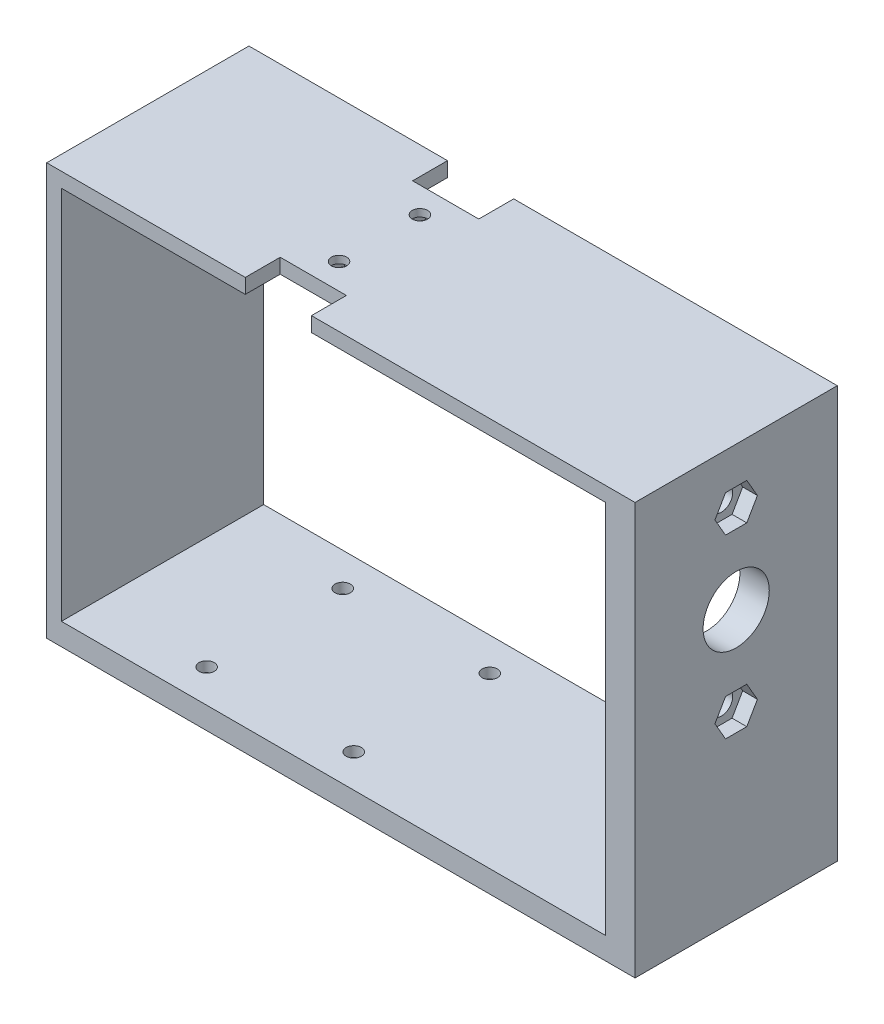
SolidWorks part; units mm, degrees
ref_plane "Front Plane" through (0, 0, 0) normal (0, 0, 1) x (1, 0, 0)
ref_plane "Top Plane" through (0, 0, 0) normal (0, 1, 0) x (1, 0, 0)
ref_plane "Right Plane" through (0, 0, 0) normal (1, 0, 0) x (0, 0, -1)
sketch "Sketch1" plane through (0, 0, 0) normal (1, 0, 0) x (0, 0, -1)
  line L1 (0, 0) -> (55, 0)
  line L2 (0, 0) -> (0, -112)
  line L3 (0, -112) -> (55, -112)
  line L4 (55, 0) -> (55, -112)
  dimension "D1" = 112
  dimension "D2" = 55
extrude "Boss-Extrude1" add sketch "Sketch1" along normal blind 160
sketch "Sketch2" plane through (0, 0, 0) normal (0, 0, 1) x (1, 0, 0)
  line L0 (160, 0) -> (0, 0) construction
  line L1 (4, -4) -> (152, -4)
  line L2 (4, -4) -> (4, -106)
  line L3 (4, -106) -> (152, -106)
  line L4 (152, -4) -> (152, -106)
  line L5 (160, 0) -> (160, -112) construction
  line L6 (160, -112) -> (0, -112) construction
  line L7 (0, 0) -> (0, -112) construction
  dimension "D1" = 4
  dimension "D2" = 8
  dimension "D3" = 6
  dimension "D4" = 4
extrude "Cut-Extrude1" cut sketch "Sketch2" against normal up to next
sketch "Sketch3" plane through (152, 0, 0) normal (-1, 0, 0) x (0, 0, 1)
  line L0 (-27.5, -106) -> (-27.5, -39) construction
  line L1 (-55, -106) -> (0, -106) construction
  line L2 (-27.5, -39) -> (-27.5, -15) construction
  line L3 (-27.5, -39) -> (0, -39) construction
  circle A0 centre (-27.5, -39) radius 9
  circle A1 centre (-27.5, -15) radius 3.05
  circle A2 centre (-27.5, -63) radius 3.05
  dimension "D3" = 6.1
  dimension "D4" = 18
  dimension "D1" = 67
  dimension "D2" = 24
extrude "Cut-Extrude2" cut sketch "Sketch3" against normal up to next
sketch "Sketch6" plane through (160, 0, 0) normal (1, 0, 0) x (0, 0, -1)
  line L0 (55, 0) -> (0, 0) construction
  line L1 (30.3868, -20) -> (33.2735, -15)
  line L2 (33.2735, -15) -> (30.3868, -10)
  line L3 (30.3868, -10) -> (24.6132, -10)
  line L4 (24.6132, -10) -> (21.7265, -15)
  line L5 (21.7265, -15) -> (24.6132, -20)
  line L6 (24.6132, -20) -> (30.3868, -20)
  line L8 (30.3868, -68) -> (33.2735, -63)
  line L9 (33.2735, -63) -> (30.3868, -58)
  line L10 (30.3868, -58) -> (24.6132, -58)
  line L11 (24.6132, -58) -> (21.7265, -63)
  line L12 (21.7265, -63) -> (24.6132, -68)
  line L13 (24.6132, -68) -> (30.3868, -68)
  circle A0 centre (27.5, -15) radius 5 construction
  circle A1 centre (27.5, -63) radius 5 construction
  dimension "D1" = 10
  dimension "D2" = 10
extrude "Cut-Extrude4" cut sketch "Sketch6" against normal blind 4
sketch "Sketch15" plane through (0, -112, 0) normal (0, -1, 0) x (-1, 0, 0)
  line L0 (0, 0) -> (0, 9) construction
  line L1 (0, 0) -> (0, 55) construction
  line L2 (0, 9) -> (-34.5, 9) construction
  line L3 (-34.5, 9) -> (-74.5, 9) construction
  line L4 (-4, 27.5) -> (-87.1996, 27.5) construction
  line L5 (-4, 55) -> (-4, 0) construction
  circle A0 centre (-34.5, 9) radius 2.075
  circle A1 centre (-74.5, 9) radius 2.075
  circle A2 centre (-74.5, 46) radius 2.075
  circle A3 centre (-34.5, 46) radius 2.075
  dimension "D3" = 4.15
  dimension "D5" = 4.15
  dimension "D1" = 34.5
  dimension "D2" = 9
  dimension "D4" = 40
extrude "Cut-Extrude11" cut sketch "Sketch15" against normal up to next
sketch "Sketch16" plane through (0, -112, 0) normal (0, -1, 0) x (-1, 0, 0)
  line L0 (-160, 0) -> (0, 0) construction
  line L1 (-38.5415, 9) -> (-36.5207, 5.5)
  line L2 (-36.5207, 5.5) -> (-32.4793, 5.5)
  line L3 (-32.4793, 5.5) -> (-30.4585, 9)
  line L4 (-30.4585, 9) -> (-32.4793, 12.5)
  line L5 (-32.4793, 12.5) -> (-36.5207, 12.5)
  line L6 (-36.5207, 12.5) -> (-38.5415, 9)
  line L7 (-34.5, 9) -> (-74.5, 9) construction
  line L8 (-4, 27.5) -> (-111.8325, 27.5) construction
  line L9 (-76.5207, 12.5) -> (-78.5415, 9)
  line L10 (-78.5415, 9) -> (-76.5207, 5.5)
  line L11 (-76.5207, 5.5) -> (-72.4793, 5.5)
  line L12 (-72.4793, 5.5) -> (-70.4585, 9)
  line L13 (-70.4585, 9) -> (-72.4793, 12.5)
  line L14 (-72.4793, 12.5) -> (-76.5207, 12.5)
  line L15 (-4, 55) -> (-4, 0) construction
  line L16 (-72.4793, 42.5) -> (-76.5207, 42.5)
  line L17 (-70.4585, 46) -> (-72.4793, 42.5)
  line L18 (-72.4793, 49.5) -> (-70.4585, 46)
  line L19 (-76.5207, 49.5) -> (-72.4793, 49.5)
  line L20 (-78.5415, 46) -> (-76.5207, 49.5)
  line L21 (-76.5207, 42.5) -> (-78.5415, 46)
  line L22 (-34.5, 46) -> (-74.5, 46) construction
  line L23 (-36.5207, 42.5) -> (-38.5415, 46)
  line L24 (-32.4793, 42.5) -> (-36.5207, 42.5)
  line L25 (-30.4585, 46) -> (-32.4793, 42.5)
  line L26 (-32.4793, 49.5) -> (-30.4585, 46)
  line L27 (-36.5207, 49.5) -> (-32.4793, 49.5)
  line L28 (-38.5415, 46) -> (-36.5207, 49.5)
  circle A0 centre (-34.5, 9) radius 3.5 construction
  circle A1 centre (-74.5, 9) radius 3.5 construction
  circle A2 centre (-74.5, 46) radius 3.5 construction
  circle A3 centre (-34.5, 46) radius 3.5 construction
  dimension "D1" = 7
  dimension "D3" = 7
  dimension "D2" = 40
extrude "Cut-Extrude12" cut sketch "Sketch16" against normal blind 3.2
sketch "Sketch17" plane through (0, 0, 0) normal (0, 1, 0) x (1, 0, 0)
  line L0 (0, 55) -> (54, 55) construction
  line L1 (160, 55) -> (0, 55) construction
  line L2 (0, 27.5) -> (88.4964, 27.5) construction
  line L3 (54, 55) -> (72, 55)
  line L4 (54, 55) -> (54, 45.5)
  line L5 (54, 45.5) -> (72, 45.5)
  line L6 (72, 55) -> (72, 45.5)
  line L7 (0, 55) -> (0, 0) construction
  line L8 (72, 0) -> (72, 9.5)
  line L9 (54, 9.5) -> (72, 9.5)
  line L10 (54, 0) -> (54, 9.5)
  line L11 (54, 0) -> (72, 0)
  dimension "D1" = 54
  dimension "D2" = 9.5
  dimension "D3" = 18
extrude "Cut-Extrude14" cut sketch "Sketch17" against normal up to next
sketch "Sketch19" plane through (0, 0, 0) normal (0, 1, 0) x (1, 0, 0)
  line L0 (63, 45.5) -> (63, 38.5) construction
  line L1 (54, 45.5) -> (72, 45.5) construction
  line L2 (0, 27.5) -> (105.3057, 27.5) construction
  line L3 (0, 55) -> (0, 0) construction
  circle A0 centre (63, 38.5) radius 2.075
  circle A1 centre (63, 16.5) radius 2.075
  dimension "D2" = 4.15
  dimension "D1" = 7
extrude "Cut-Extrude15" cut sketch "Sketch19" against normal up to next
sketch "Sketch20" plane through (0, -4, 0) normal (0, -1, 0) x (1, 0, 0)
  line L0 (54, -9.5) -> (72, -9.5) construction
  line L1 (67.0415, -16.5) -> (65.0207, -13)
  line L2 (65.0207, -13) -> (60.9793, -13)
  line L3 (60.9793, -13) -> (58.9585, -16.5)
  line L4 (58.9585, -16.5) -> (60.9793, -20)
  line L5 (60.9793, -20) -> (65.0207, -20)
  line L6 (65.0207, -20) -> (67.0415, -16.5)
  line L7 (0, -27.5) -> (111.0566, -27.5) construction
  line L8 (0, -55) -> (0, 0) construction
  line L9 (65.0207, -35) -> (67.0415, -38.5)
  line L10 (60.9793, -35) -> (65.0207, -35)
  line L11 (58.9585, -38.5) -> (60.9793, -35)
  line L12 (60.9793, -42) -> (58.9585, -38.5)
  line L13 (65.0207, -42) -> (60.9793, -42)
  line L14 (67.0415, -38.5) -> (65.0207, -42)
  circle A0 centre (63, -16.5) radius 3.5 construction
  circle A1 centre (63, -38.5) radius 3.5 construction
  dimension "D1" = 7
extrude "Cut-Extrude16" cut sketch "Sketch20" against normal blind 2
